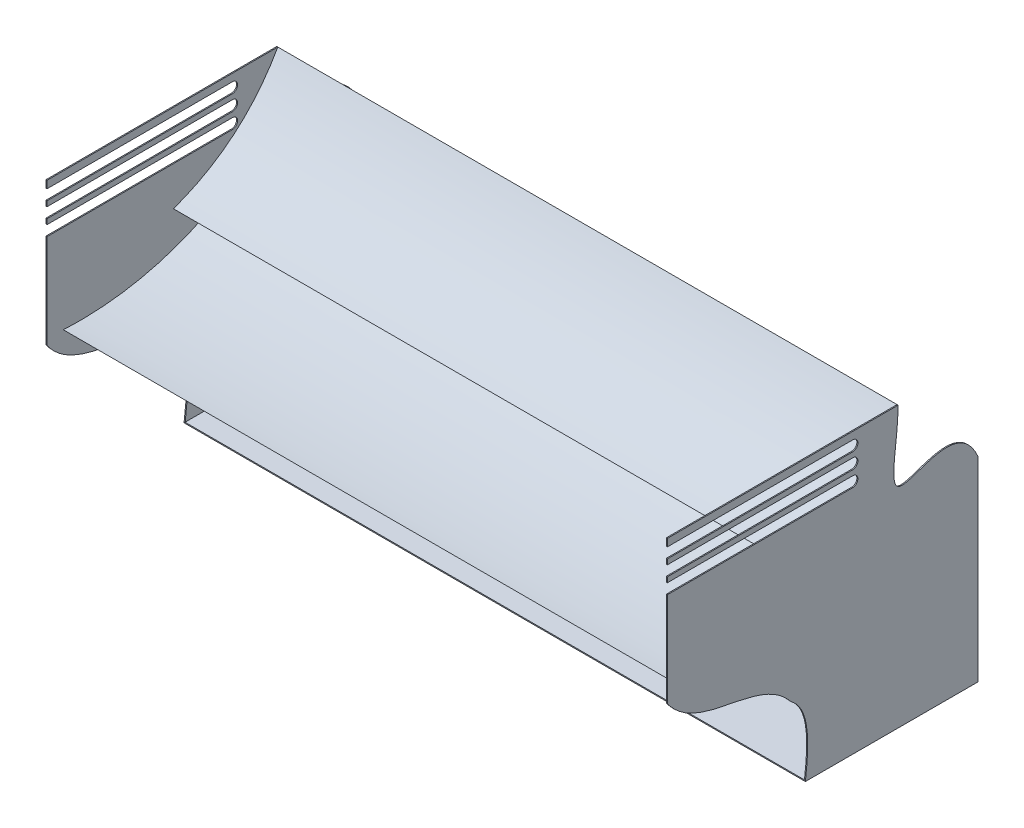
SolidWorks part; units mm, degrees
ref_plane "Front Plane" through (0, 0, 0) normal (0, 0, 1) x (1, 0, 0)
ref_plane "Top Plane" through (0, 0, 0) normal (0, 1, 0) x (1, 0, 0)
ref_plane "Right Plane" through (0, 0, 0) normal (1, 0, 0) x (0, 0, -1)
sketch "Sketch3" plane through (0, 0, 0) normal (1, 0, 0) x (0, 0, -1)
  line L0 (0, 0) -> (0, 53215.7306) construction
  line L1 (0, 0) -> (1560.3678, 0) construction
  line L2 (566.0212, 618.0336) -> (566.0212, 753.5664) construction
  line L3 (338.5701, 0) -> (762, 0)
  line L4 (0, 216.9745) -> (0, 685.8)
  line L5 (0, 685.8) -> (566.0212, 685.8)
  line L6 (762, 0) -> (762, 478.6438)
  line L7 (591.3318, 510.8493) -> (528.9855, 510.8493) construction
  line L8 (124.7436, 216.9745) -> (-124.7436, 216.9745) construction
  spline S0 degree 3 poles (566.0212, 685.8) (566.0212, 609.5628) (511.0186, 418.0648) (711.566, 596.214) (762, 478.6438) knots 0 0 0 0 0.433377 1 1 1 1
  spline S1 degree 3 poles (0, 216.9745) (268.1536, 216.9745) (370.7959, 243.0789) (338.5701, 0) knots 0 0 0 0 1 1 1 1
  dimension "D1" = 685.8
  dimension "D2" = 762
extrude "Boss-Extrude1" add sketch "Sketch3" against normal blind 2.54 from offset 762
mirror "Mirror1" about plane through (0, 0, 0) normal (1, 0, 0) of bodies 101
sketch "Sketch8" plane through (0, 0, 0) normal (1, 0, 0) x (0, 0, -1)
  spline S0 degree 2 poles (566.0212, 685.8) (478.9461, 530.5926) (310.0418, 470.2609) knots 0 0 0 1 1 1
  spline S1 degree 2 poles (566.0212, 685.8) (535.193, 473.792) (310.0418, 470.2609) knots 0 0 0 1 1 1
  spline S2 degree 2 poles (493.8054, 481.1775) (291.8202, 335.218) (39.8548, 348.3583) knots 0 0 0 1 1 1
  spline S3 degree 2 poles (493.8054, 481.1775) (323.5984, 237.8631) (39.8548, 348.3583) knots 0 0 0 1 1 1
extrude "Boss-Extrude3" add sketch "Sketch8" along normal up to body (759.46 mm away) and the other way through all separate body
sketch "Sketch13" plane through (0, 0, 0) normal (0, 1, 0) x (1, 0, 0)
  line L1 (-762, 338.5701) -> (762, 338.5701)
  line L2 (-762, 338.5701) -> (-762, 762)
  line L3 (-762, 762) -> (762, 762)
  line L4 (762, 338.5701) -> (762, 762)
extrude "Boss-Extrude4" add sketch "Sketch13" along normal blind 2.54 separate body
sketch "Sketch16" plane through (0, 0, 0) normal (1, 0, 0) x (0, 0, -1)
  line L0 (0, 667.6702) -> (454.6874, 667.6702)
  line L1 (0, 685.8) -> (0, 216.9745) construction
  line L2 (0, 642.2702) -> (454.6874, 642.2702)
  line L3 (467.3874, 654.9702) -> (467.3874, -49345.0298) construction
  line L4 (467.3874, 487.2093) -> (-49532.6126, 487.2093) construction
  line L5 (0, 604.1702) -> (454.6874, 604.1702)
  line L6 (0, 629.5702) -> (454.6874, 629.5702)
  line L7 (0, 566.0702) -> (454.6874, 566.0702)
  line L8 (0, 591.4702) -> (454.6874, 591.4702)
  arc A0 (0, 667.6702) -> (0, 642.2702) centre (0, 654.9702) ccw
  arc A1 (454.6874, 667.6702) -> (454.6874, 642.2702) centre (454.6874, 654.9702) cw
  arc A2 (0, 629.5702) -> (0, 604.1702) centre (0, 616.8702) ccw
  arc A3 (0, 591.4702) -> (0, 566.0702) centre (0, 578.7702) ccw
  arc A4 (454.6874, 629.5702) -> (454.6874, 604.1702) centre (454.6874, 616.8702) cw
  arc A5 (454.6874, 591.4702) -> (454.6874, 566.0702) centre (454.6874, 578.7702) cw
  point P10 (467.3874, 654.9702)
  dimension "D1" = 25.4
  dimension "D2" = 3
extrude "Cut-Extrude1" cut sketch "Sketch16" against normal through all both and the other way through all
sketch "Sketch17" plane through (0, 0, 0) normal (1, 0, 0) x (0, 0, -1)
  line L0 (0, 566.0702) -> (0, 216.9745) construction
  line L1 (0, 334.7123) -> (0, 103.6431)
  line L2 (0, 103.6431) -> (302.9996, 187.6548)
  spline S0 degree 3 poles (302.9996, 187.6548) (225.2185, 285.7396) (76.8008, 227.8512) (0, 334.7123) knots 0 0 0 0 1 1 1 1
  spline S1 degree 3 poles (0, 216.9745) (267.216, 216.9745) (370.0761, 242.8967) (338.9032, 2.54) knots 0 0 0 0 0.996503 0.996503 0.996503 0.996503 construction
extrude "Cut-Extrude2" cut sketch "Sketch17" against normal through all both and the other way through all
